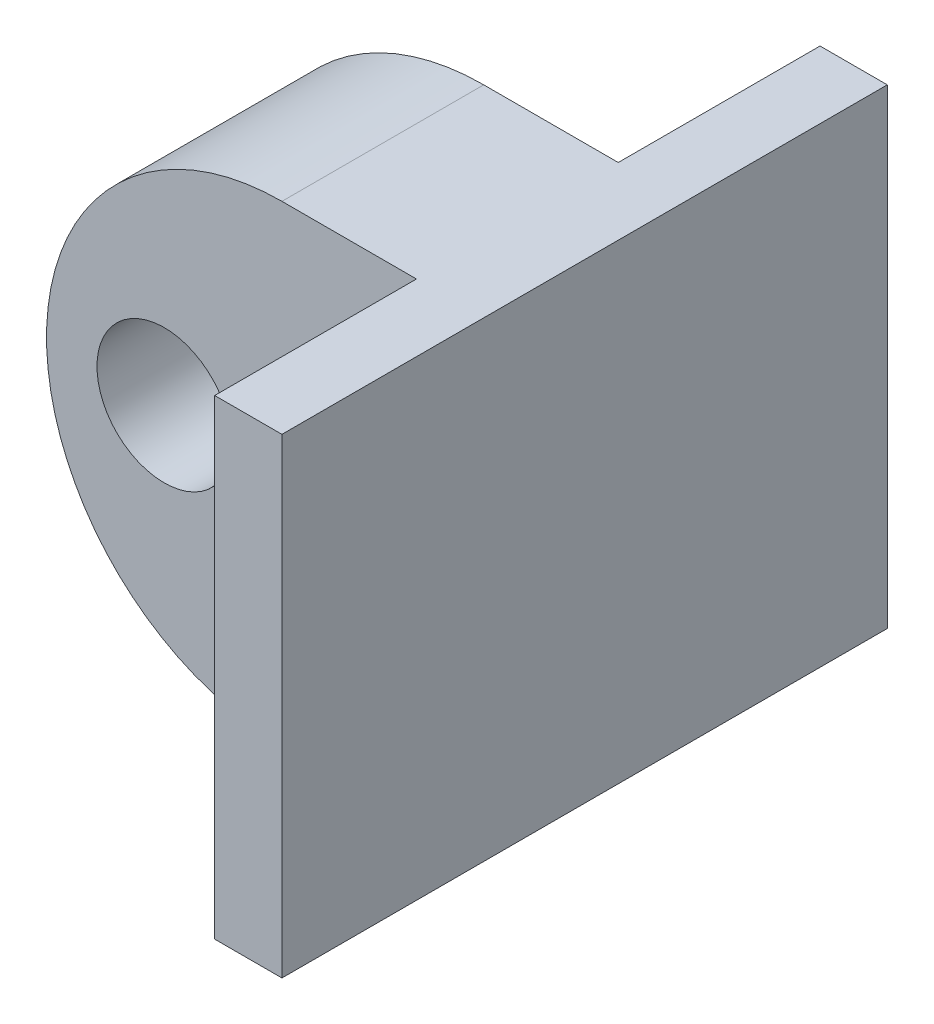
SolidWorks part; units mm, degrees
ref_plane "Front Plane" through (0, 0, 0) normal (0, 0, 1) x (1, 0, 0)
ref_plane "Top Plane" through (0, 0, 0) normal (0, 1, 0) x (1, 0, 0)
ref_plane "Right Plane" through (0, 0, 0) normal (1, 0, 0) x (0, 0, -1)
sketch "Sketch1" plane through (0, 0, 0) normal (0, 0, 1) x (1, 0, 0)
  line L1 (0, 35) -> (20, 35)
  line L3 (0, -35) -> (20, -35)
  line L4 (20, 35) -> (20, -35)
  arc A0 (0, 35) -> (0, -35) centre (0, 0) ccw
  circle A1 centre (-17.5, 0) radius 10
  dimension "D2" = 20
  dimension "D1" = 70
  dimension "D3" = 20
extrude "Boss-Extrude1" add sketch "Sketch1" along normal blind 30
sketch "Sketch2" plane through (20, 0, 0) normal (1, 0, 0) x (0, 0, -1)
  line L5 (30, 35) -> (-60, 35)
  line L6 (30, 35) -> (30, -35)
  line L7 (30, -35) -> (-60, -35)
  line L8 (-60, 35) -> (-60, -35)
  point P10 (0, 0)
  dimension "D3" = 90
extrude "Boss-Extrude2" add sketch "Sketch2" along normal blind 10
